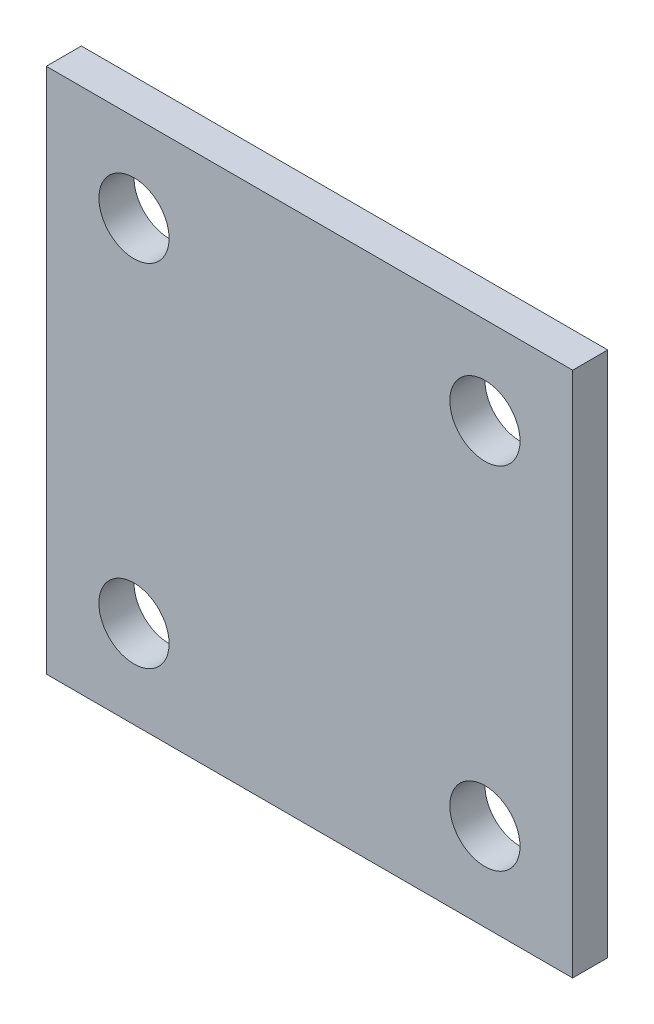
SolidWorks part; units mm, degrees
ref_plane "Front Plane" through (0, 0, 0) normal (0, 0, 1) x (1, 0, 0)
ref_plane "Top Plane" through (0, 0, 0) normal (0, 1, 0) x (1, 0, 0)
ref_plane "Right Plane" through (0, 0, 0) normal (1, 0, 0) x (0, 0, -1)
sketch "Sketch1" plane through (0, 0, 0) normal (0, 0, 1) x (1, 0, 0)
  line L1 (-750, 750) -> (750, 750)
  line L2 (-750, 750) -> (-750, -750)
  line L3 (-750, -750) -> (750, -750)
  line L4 (750, 750) -> (750, -750)
  line L5 (-750, 750) -> (750, -750) construction
  line L6 (-750, -750) -> (750, 750) construction
  line L7 (500, -500) -> (-500, -500) construction
  line L8 (500, -500) -> (500, 500) construction
  line L9 (500, 500) -> (-500, 500) construction
  line L10 (-500, -500) -> (-500, 500) construction
  line L11 (500, -500) -> (-500, 500) construction
  line L12 (500, 500) -> (-500, -500) construction
  circle A1 centre (-500, 500) radius 100
  circle A2 centre (500, 500) radius 100
  circle A3 centre (500, -500) radius 100
  circle A4 centre (-500, -500) radius 100
  dimension "D5" = 200
  dimension "D1" = 1500
  dimension "D2" = 1500
  dimension "D4" = 1000
extrude "Boss-Extrude1" add sketch "Sketch1" along normal blind 100
